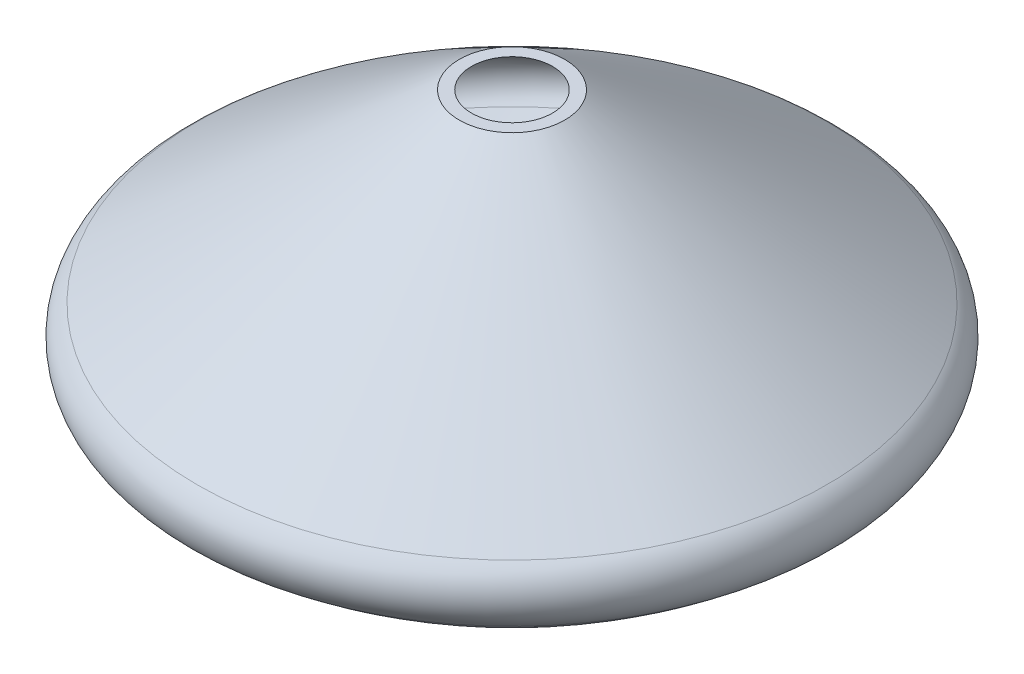
SolidWorks part; units mm, degrees
material "Glass"
ref_plane "Front Plane" through (0, 0, 0) normal (1, 0, 0) x (0, 1, 0)
ref_plane "Top Plane" through (0, 0, 0) normal (0, 0, 1) x (0, 1, 0)
ref_plane "Right Plane" through (0, 0, 0) normal (0, 1, 0) x (-1, 0, 0)
sketch "Sketch1" plane through (0, 0, 0) normal (1, 0, 0) x (0, 1, 0)
  line L0 (0, 77.6836) -> (0, -74.9092) construction
  line L1 (-178.6949, 0) -> (99.048, 0) construction
  line L2 (0, 15) -> (-52.6207, 89.5947)
  line L3 (44.2042, 106.1799) -> (44.2042, -116.4289) construction
  line L4 (44.2042, -0.3) -> (-172.1736, 11.0399) construction
  line L5 (-100.7922, 0) -> (0, 0)
  line L6 (0, 0) -> (0, 15)
  arc A0 (-52.6207, 89.5947) -> (-68.5697, 90.1161) centre (-60.7922, 83.8303) ccw
  arc A1 (-68.5697, 90.1161) -> (-100.7922, 0) centre (44.2042, -1.027) ccw
  point P9 (-60.4654, 93.825)
  dimension "D4" = 40
  dimension "D5" = 10
  dimension "D6" = 145
  dimension "D7" = 3
  dimension "D1" = 215.2
  dimension "D2" = 30
  dimension "D3" = 187.65
revolve "Revolve1" add sketch "Sketch1" angle 360 about L1
shell "Shell1" thickness 2
ref_plane "Plane1" through (0, -110, 0) normal (0, 1, 0) x (-1, 0, 0)
sketch "Sketch3" plane through (0, -110, 0) normal (0, 1, 0) x (-1, 0, 0)
  line L0 (0, 98.5) -> (0, -98.5) construction
  line L1 (98.5, 0) -> (-98.5, 0) construction
  line L2 (1, 98.5) -> (1, -98.5)
  line L3 (-1, 98.5) -> (-1, -98.5)
  line L4 (98.5, 1) -> (-98.5, 1)
  line L5 (98.5, -1) -> (-98.5, -1)
  line L6 (6.5, 98.5) -> (6.5, -98.5)
  line L7 (8.5, 98.5) -> (8.5, -98.5)
  line L8 (14, 98.5) -> (14, -98.5)
  line L9 (16, 98.5) -> (16, -98.5)
  line L10 (21.5, 98.5) -> (21.5, -98.5)
  line L11 (23.5, 98.5) -> (23.5, -98.5)
  line L12 (29, 98.5) -> (29, -98.5)
  line L13 (31, 98.5) -> (31, -98.5)
  line L14 (36.5, 98.5) -> (36.5, -98.5)
  line L15 (38.5, 98.5) -> (38.5, -98.5)
  line L16 (44, 98.5) -> (44, -98.5)
  line L17 (46, 98.5) -> (46, -98.5)
  line L18 (51.5, 98.5) -> (51.5, -98.5)
  line L19 (53.5, 98.5) -> (53.5, -98.5)
  line L20 (59, 98.5) -> (59, -98.5)
  line L21 (61, 98.5) -> (61, -98.5)
  line L22 (66.5, 98.5) -> (66.5, -98.5)
  line L23 (68.5, 98.5) -> (68.5, -98.5)
  line L24 (74, 98.5) -> (74, -98.5)
  line L25 (76, 98.5) -> (76, -98.5)
  line L26 (81.5, 98.5) -> (81.5, -98.5)
  line L27 (83.5, 98.5) -> (83.5, -98.5)
  line L28 (89, 98.5) -> (89, -98.5)
  line L29 (91, 98.5) -> (91, -98.5)
  line L30 (96.5, 98.5) -> (96.5, -98.5)
  line L31 (98.5, 98.5) -> (98.5, -98.5)
  line L32 (98.5, 6.5) -> (-98.5, 6.5)
  line L33 (98.5, 8.5) -> (-98.5, 8.5)
  line L34 (98.5, 14) -> (-98.5, 14)
  line L35 (98.5, 16) -> (-98.5, 16)
  line L36 (98.5, 21.5) -> (-98.5, 21.5)
  line L37 (98.5, 23.5) -> (-98.5, 23.5)
  line L38 (98.5, 29) -> (-98.5, 29)
  line L39 (98.5, 31) -> (-98.5, 31)
  line L40 (98.5, 36.5) -> (-98.5, 36.5)
  line L41 (98.5, 38.5) -> (-98.5, 38.5)
  line L42 (98.5, 44) -> (-98.5, 44)
  line L43 (98.5, 46) -> (-98.5, 46)
  line L44 (98.5, 51.5) -> (-98.5, 51.5)
  line L45 (98.5, 53.5) -> (-98.5, 53.5)
  line L46 (98.5, 59) -> (-98.5, 59)
  line L47 (98.5, 61) -> (-98.5, 61)
  line L48 (98.5, 66.5) -> (-98.5, 66.5)
  line L49 (98.5, 68.5) -> (-98.5, 68.5)
  line L50 (98.5, 74) -> (-98.5, 74)
  line L51 (98.5, 76) -> (-98.5, 76)
  line L52 (98.5, 81.5) -> (-98.5, 81.5)
  line L53 (98.5, 83.5) -> (-98.5, 83.5)
  line L54 (98.5, 89) -> (-98.5, 89)
  line L55 (98.5, 91) -> (-98.5, 91)
  line L56 (98.5, 96.5) -> (-98.5, 96.5)
  line L57 (98.5, 98.5) -> (-98.5, 98.5)
  line L58 (98.5, -8.5) -> (-98.5, -8.5)
  line L59 (98.5, -6.5) -> (-98.5, -6.5)
  line L60 (98.5, -16) -> (-98.5, -16)
  line L61 (98.5, -14) -> (-98.5, -14)
  line L62 (98.5, -23.5) -> (-98.5, -23.5)
  line L63 (98.5, -21.5) -> (-98.5, -21.5)
  line L64 (98.5, -31) -> (-98.5, -31)
  line L65 (98.5, -29) -> (-98.5, -29)
  line L66 (98.5, -38.5) -> (-98.5, -38.5)
  line L67 (98.5, -36.5) -> (-98.5, -36.5)
  line L68 (98.5, -46) -> (-98.5, -46)
  line L69 (98.5, -44) -> (-98.5, -44)
  line L70 (98.5, -53.5) -> (-98.5, -53.5)
  line L71 (98.5, -51.5) -> (-98.5, -51.5)
  line L72 (98.5, -61) -> (-98.5, -61)
  line L73 (98.5, -59) -> (-98.5, -59)
  line L74 (98.5, -68.5) -> (-98.5, -68.5)
  line L75 (98.5, -66.5) -> (-98.5, -66.5)
  line L76 (98.5, -76) -> (-98.5, -76)
  line L77 (98.5, -74) -> (-98.5, -74)
  line L78 (98.5, -83.5) -> (-98.5, -83.5)
  line L79 (98.5, -81.5) -> (-98.5, -81.5)
  line L80 (98.5, -91) -> (-98.5, -91)
  line L81 (98.5, -89) -> (-98.5, -89)
  line L82 (98.5, -98.5) -> (-98.5, -98.5)
  line L83 (98.5, -96.5) -> (-98.5, -96.5)
  line L84 (-6.5, 98.5) -> (-6.5, -98.5)
  line L85 (-8.5, 98.5) -> (-8.5, -98.5)
  line L86 (-14, 98.5) -> (-14, -98.5)
  line L87 (-16, 98.5) -> (-16, -98.5)
  line L88 (-21.5, 98.5) -> (-21.5, -98.5)
  line L89 (-23.5, 98.5) -> (-23.5, -98.5)
  line L90 (-29, 98.5) -> (-29, -98.5)
  line L91 (-31, 98.5) -> (-31, -98.5)
  line L92 (-36.5, 98.5) -> (-36.5, -98.5)
  line L93 (-38.5, 98.5) -> (-38.5, -98.5)
  line L94 (-44, 98.5) -> (-44, -98.5)
  line L95 (-46, 98.5) -> (-46, -98.5)
  line L96 (-51.5, 98.5) -> (-51.5, -98.5)
  line L97 (-53.5, 98.5) -> (-53.5, -98.5)
  line L98 (-59, 98.5) -> (-59, -98.5)
  line L99 (-61, 98.5) -> (-61, -98.5)
  line L100 (-66.5, 98.5) -> (-66.5, -98.5)
  line L101 (-68.5, 98.5) -> (-68.5, -98.5)
  line L102 (-74, 98.5) -> (-74, -98.5)
  line L103 (-76, 98.5) -> (-76, -98.5)
  line L104 (-81.5, 98.5) -> (-81.5, -98.5)
  line L105 (-83.5, 98.5) -> (-83.5, -98.5)
  line L106 (-89, 98.5) -> (-89, -98.5)
  line L107 (-91, 98.5) -> (-91, -98.5)
  line L108 (-96.5, 98.5) -> (-96.5, -98.5)
  line L109 (-98.5, 98.5) -> (-98.5, -98.5)
  dimension "D1" = 1
  dimension "D2" = 1
  dimension "D3" = 1
  dimension "D4" = 1
  dimension "D7" = 16
  dimension "D8" = 16
  dimension "D11" = 16
  dimension "D12" = 16
  dimension "D5" = 14
  dimension "D6" = 14
  dimension "D9" = 14
  dimension "D10" = 14
sketch "Sketch4" [suppressed] plane through (0, -110, 0) normal (0, 1, 0) x (-1, 0, 0)
  line L0 (98.5, -1) -> (-98.5, -1) construction
  line L1 (98.5, 1) -> (-98.5, 1) construction
  line L2 (-1, 98.5) -> (-1, -98.5) construction
  line L3 (1, 98.5) -> (1, -98.5) construction
  line L4 (98.5, 8.5) -> (-98.5, 8.5) construction
  line L5 (98.5, 6.5) -> (-98.5, 6.5) construction
  line L6 (6.5, 98.5) -> (6.5, -98.5) construction
  line L7 (8.5, 98.5) -> (8.5, -98.5) construction
  line L8 (8.5, -1) -> (-1, -1)
  line L9 (6.5, 1) -> (1, 1)
  line L10 (-1, 8.5) -> (-1, -1)
  line L11 (1, 6.5) -> (1, 1)
  line L12 (8.5, 8.5) -> (-1, 8.5)
  line L13 (6.5, 6.5) -> (1, 6.5)
  line L14 (6.5, 6.5) -> (6.5, 1)
  line L15 (8.5, 8.5) -> (8.5, -1)
wrap "Wrap1" [suppressed] sketch "Sketch4" source sketch "Sketch4" thickness 2 parameters "D1"=2
sketch "Sketch5" [suppressed] plane through (0, -110, 0) normal (0, 1, 0) x (-1, 0, 0)
  circle A0 centre (0, 0) radius 90.1161 construction
  circle A1 centre (0, 0) radius 90.1161
ref_plane "Plane2" through (0, -60, 0) normal (0, 1, 0) x (-1, 0, 0)
sketch "Sketch6" plane through (0, 0, 0) normal (1, 0, 0) x (0, 1, 0)
  arc A0 (-68.5697, 90.1161) -> (-100.7922, 0) centre (44.2042, -1.027) ccw
  arc A1 (-100.7922, 0) -> (-68.5697, -90.1161) centre (44.2042, 1.027) ccw
  arc A2 (-100.7922, 0) -> (-68.5697, -90.1161) centre (44.2042, 1.027) ccw construction
  arc A3 (-68.5697, 90.1161) -> (-100.7922, 0) centre (44.2042, -1.027) ccw construction
  arc A4 (-69.3475, 90.7446) -> (-101.7922, 0) centre (44.2042, -1.027) ccw
  arc A5 (-101.7922, 0) -> (-69.3475, -90.7446) centre (44.2042, 1.027) ccw
  dimension "D1" = 1
ref_plane "Plane3" [suppressed] through (0, -68.5697, 90.1161) normal (0, -0.6286, -0.7778) x (0, 0.7778, -0.6286)
sketch "Sketch7" [suppressed] plane through (0, -68.5697, 90.1161) normal (0, -0.6286, -0.7778) x (0, 0.7778, -0.6286)
  circle A0 centre (-1, 0) radius 1
  ellipse E0 centre (56.6445, 0) end of major axis (56.6445, 90.1161) minor radius 56.6445 construction
  point P3 (0, 0)
  dimension "D1" = 2
sweep "Sweep3" [suppressed] add profiles "Sketch7" path "Sketch6"
sketch "Sketch14" plane through (0, -110, 0) normal (0, 1, 0) x (-1, 0, 0)
  line L0 (-97.5, 97.5) -> (97.5, 97.5)
  line L1 (0, 97.5) -> (0, -97.5)
  line L2 (97.5, 97.5) -> (97.5, -97.5)
  line L3 (-97.5, 0) -> (97.5, 0)
  line L4 (97.5, -97.5) -> (-97.5, -97.5)
  line L5 (-97.5, -97.5) -> (-97.5, 97.5)
  line L6 (7.5, 97.5) -> (7.5, -97.5)
  line L7 (15, 97.5) -> (15, -97.5)
  line L8 (22.5, 97.5) -> (22.5, -97.5)
  line L9 (30, 97.5) -> (30, -97.5)
  line L10 (37.5, 97.5) -> (37.5, -97.5)
  line L11 (45, 97.5) -> (45, -97.5)
  line L12 (52.5, 97.5) -> (52.5, -97.5)
  line L13 (60, 97.5) -> (60, -97.5)
  line L14 (67.5, 97.5) -> (67.5, -97.5)
  line L15 (75, 97.5) -> (75, -97.5)
  line L16 (82.5, 97.5) -> (82.5, -97.5)
  line L17 (90, 97.5) -> (90, -97.5)
  line L19 (97.5, 97.5) -> (97.5, -97.5)
  line L20 (-90, -97.5) -> (-90, 97.5)
  line L21 (-82.5, -97.5) -> (-82.5, 97.5)
  line L22 (-75, -97.5) -> (-75, 97.5)
  line L23 (-67.5, -97.5) -> (-67.5, 97.5)
  line L24 (-60, -97.5) -> (-60, 97.5)
  line L25 (-52.5, -97.5) -> (-52.5, 97.5)
  line L26 (-45, -97.5) -> (-45, 97.5)
  line L27 (-37.5, -97.5) -> (-37.5, 97.5)
  line L28 (-30, -97.5) -> (-30, 97.5)
  line L29 (-22.5, -97.5) -> (-22.5, 97.5)
  line L30 (-15, -97.5) -> (-15, 97.5)
  line L33 (-7.5, -97.5) -> (-7.5, 97.5)
  line L34 (0, -97.5) -> (0, 97.5)
  line L35 (-97.5, 90) -> (97.5, 90)
  line L36 (-97.5, 82.5) -> (97.5, 82.5)
  line L37 (-97.5, 75) -> (97.5, 75)
  line L38 (-97.5, 67.5) -> (97.5, 67.5)
  line L39 (-97.5, 60) -> (97.5, 60)
  line L40 (-97.5, 52.5) -> (97.5, 52.5)
  line L41 (-97.5, 45) -> (97.5, 45)
  line L42 (-97.5, 37.5) -> (97.5, 37.5)
  line L43 (-97.5, 30) -> (97.5, 30)
  line L44 (-97.5, 22.5) -> (97.5, 22.5)
  line L45 (-97.5, 15) -> (97.5, 15)
  line L46 (-97.5, 7.5) -> (97.5, 7.5)
  line L47 (-97.5, 0) -> (97.5, 0)
  line L48 (-97.5, -7.5) -> (97.5, -7.5)
  line L49 (-97.5, -15) -> (97.5, -15)
  line L50 (-97.5, -22.5) -> (97.5, -22.5)
  line L51 (-97.5, -30) -> (97.5, -30)
  line L52 (-97.5, -37.5) -> (97.5, -37.5)
  line L53 (-97.5, -45) -> (97.5, -45)
  line L54 (-97.5, -52.5) -> (97.5, -52.5)
  line L55 (-97.5, -60) -> (97.5, -60)
  line L56 (-97.5, -67.5) -> (97.5, -67.5)
  line L81 (-97.5, -75) -> (97.5, -75)
  line L82 (-97.5, -82.5) -> (97.5, -82.5)
  line L83 (-97.5, -90) -> (97.5, -90)
  line L84 (-97.5, -97.5) -> (97.5, -97.5)
  point P4 (0, 0)
  point P5 (0, 0)
  dimension "D1" = 14
  dimension "D2" = 195
  dimension "D4" = 7.5
  dimension "D5" = 14
  dimension "D6" = 27
  dimension "D3" = 97.5
